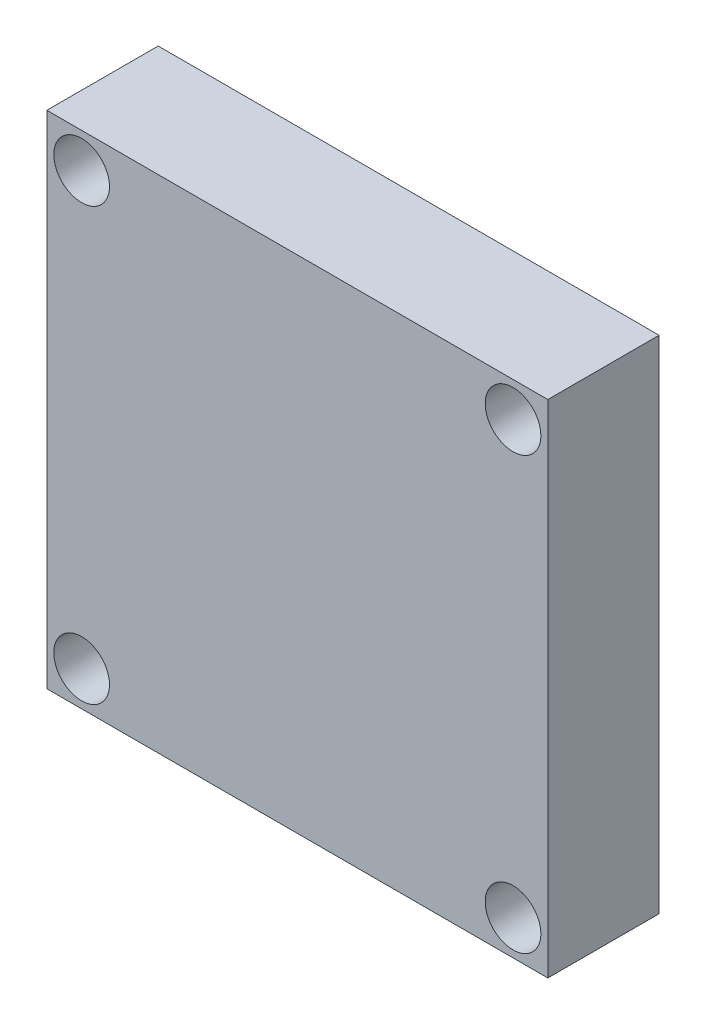
SolidWorks part; units mm, degrees
ref_plane "Front Plane" through (0, 0, 0) normal (0, 0, 1) x (1, 0, 0)
ref_plane "Top Plane" through (0, 0, 0) normal (0, 1, 0) x (1, 0, 0)
ref_plane "Right Plane" through (0, 0, 0) normal (1, 0, 0) x (0, 0, -1)
sketch "Sketch1" plane through (0, 0, 0) normal (0, 0, 1) x (1, 0, 0)
  line L1 (-18, -18) -> (18, -18)
  line L2 (-18, -18) -> (-18, 18)
  line L3 (-18, 18) -> (18, 18)
  line L4 (18, -18) -> (18, 18)
  line L5 (-18, -18) -> (18, 18) construction
  line L6 (-18, 18) -> (18, -18) construction
  line L7 (-15.5, -15.5) -> (15.5, -15.5) construction
  line L8 (-15.5, -15.5) -> (-15.5, 15.5) construction
  line L9 (-15.5, 15.5) -> (15.5, 15.5) construction
  line L10 (15.5, -15.5) -> (15.5, 15.5) construction
  line L11 (-15.5, -15.5) -> (15.5, 15.5) construction
  line L12 (-15.5, 15.5) -> (15.5, -15.5) construction
  circle A0 centre (-15.5, 15.5) radius 2
  circle A1 centre (15.5, 15.5) radius 2
  circle A2 centre (15.5, -15.5) radius 2
  circle A3 centre (-15.5, -15.5) radius 2
  point P0 (0, 0)
  point P6 (0, 0)
  point P15 (15.5, 0)
  dimension "D3" = 4
  dimension "D4" = 4
  dimension "D5" = 4
  dimension "D6" = 4
  dimension "D1" = 36
  dimension "D2" = 36
  dimension "D7" = 31
  dimension "D8" = 31
extrude "Boss-Extrude1" add sketch "Sketch1" along normal mid plane 8 contours A3 L1 A2 L4 A1 L3 A0 L2
